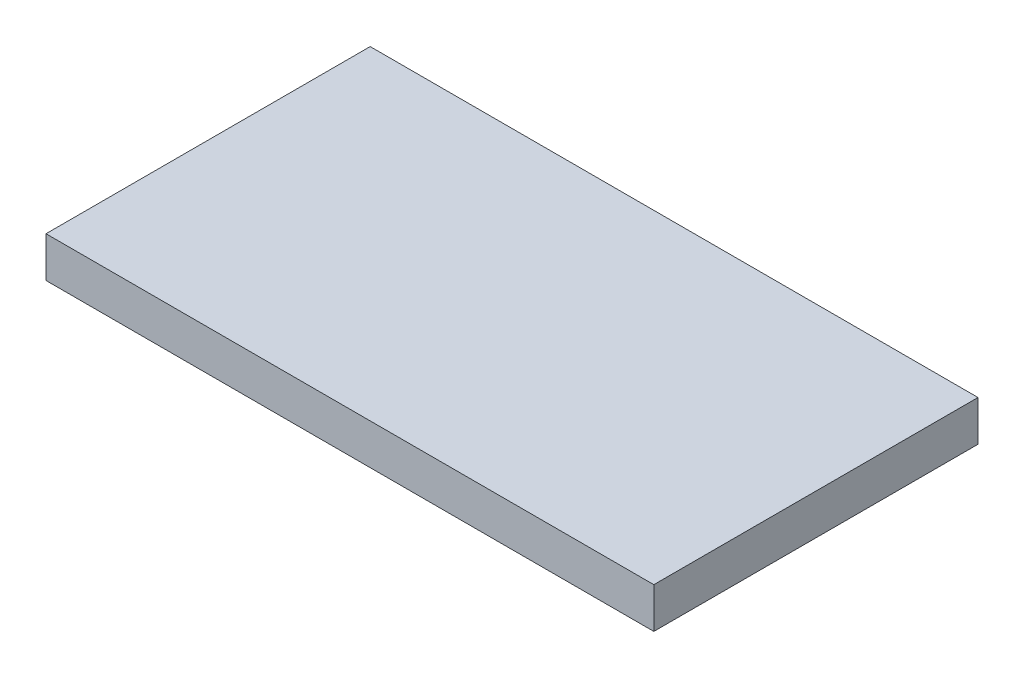
SolidWorks part; units mm, degrees
material "AISI 1020 Steel, Cold Rolled"
ref_plane "Front Plane" through (0, 0, 0) normal (0, 0, 1) x (1, 0, 0)
ref_plane "Top Plane" through (0, 0, 0) normal (0, 1, 0) x (1, 0, 0)
ref_plane "Right Plane" through (0, 0, 0) normal (1, 0, 0) x (0, 0, -1)
sketch "Sketch2" plane through (0, 0, 0) normal (0, 1, 0) x (1, 0, 0)
  line L1 (-750, -400) -> (750, -400)
  line L2 (-750, -400) -> (-750, 400)
  line L3 (-750, 400) -> (750, 400)
  line L4 (750, -400) -> (750, 400)
  line L5 (-750, -400) -> (750, 400) construction
  line L6 (-750, 400) -> (750, -400) construction
  point P0 (0, 0)
  dimension "D1" = 800
  dimension "D2" = 1500
extrude "Boss-Extrude1" add sketch "Sketch2" along normal blind 100
sketch "Sketch3" plane through (0, 100, 0) normal (0, 1, 0) x (1, 0, 0)
  line L0 (750, 0) -> (-428.6975, 0) construction
  line L1 (750, -400) -> (750, 400) construction
  line L2 (-278.0173, 48.9) -> (-278.0173, 0) construction
  dimension "D1" = 48.9
sketch "Sketch4" plane through (0, 100, 0) normal (0, 1, 0) x (1, 0, 0)
  line L0 (0, 0) -> (-608.1756, 0.0024) construction
sketch "Sketch5" plane through (0, 100, 0) normal (0, 1, 0) x (1, 0, 0)
  line L0 (750, 400) -> (-750, 400) construction
  line L1 (346.827, 400) -> (750, 400)
  line L2 (346.827, 400) -> (346.827, -400)
  line L3 (346.827, -400) -> (750, -400)
  line L4 (750, 400) -> (750, -400)
